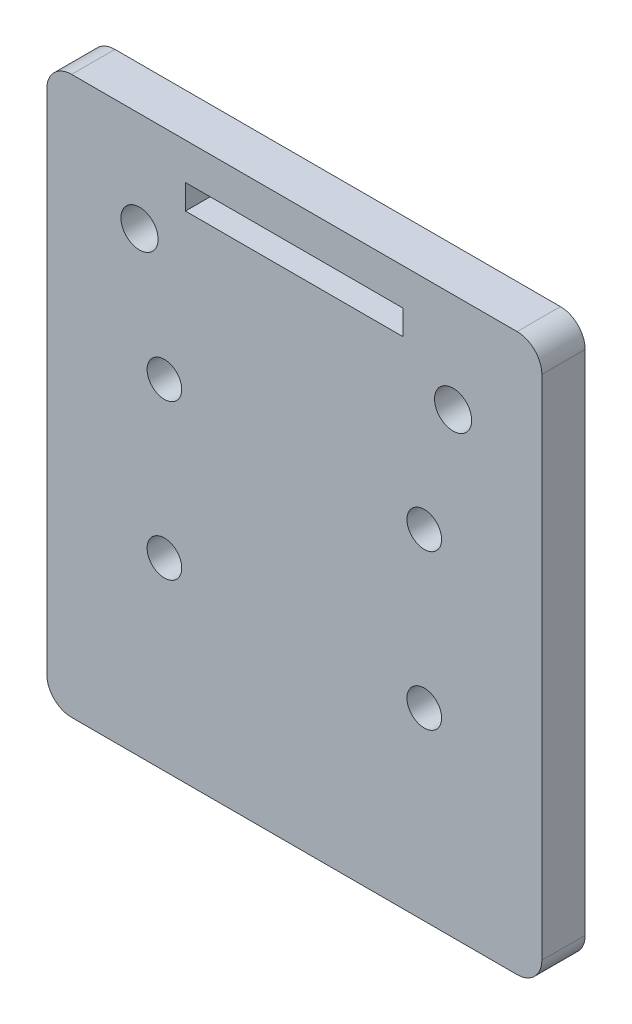
SolidWorks part; units mm, degrees
ref_plane "Front Plane" through (0, 0, 0) normal (0, 0, 1) x (1, 0, 0)
ref_plane "Top Plane" through (0, 0, 0) normal (0, 1, 0) x (1, 0, 0)
ref_plane "Right Plane" through (0, 0, 0) normal (1, 0, 0) x (0, 0, -1)
sketch "Sketch1" plane through (0, 0, 0) normal (0, 0, 1) x (1, 0, 0)
  line L1 (-2, 0) -> (-38, 0)
  line L2 (0, 2) -> (0, 43)
  line L3 (-2, 45) -> (-38, 45)
  line L4 (-40, 2) -> (-40, 43)
  arc A0 (-2, 0) -> (0, 2) centre (-2, 2) ccw
  arc A1 (-40, 2) -> (-38, 0) centre (-38, 2) ccw
  arc A2 (-2, 45) -> (0, 43) centre (-2, 43) cw
  arc A3 (-38, 45) -> (-40, 43) centre (-38, 43) ccw
  point P7 (0, 0)
  point P10 (-40, 0)
  point P13 (0, 45)
  point P16 (-40, 45)
  dimension "D3" = 2
  dimension "D1" = 40
  dimension "D2" = 45
extrude "Boss-Extrude1" add sketch "Sketch1" along normal blind 3.5 contours L2 A2 L3 A3 L4 A1 L1 A0
sketch "Sketch2" plane through (0, 0, 3.5) normal (0, 0, 1) x (1, 0, 0)
  line L0 (-20, 45) -> (-20, 0)
  line L1 (-2, 45) -> (-38, 45) construction
  line L2 (-2, 0) -> (-38, 0) construction
  line L4 (-28.8, 42.0339) -> (-11.2, 42.0339)
  line L5 (-28.8, 42.0339) -> (-28.8, 40.0339)
  line L6 (-28.8, 40.0339) -> (-11.2, 40.0339)
  line L7 (-11.2, 42.0339) -> (-11.2, 40.0339)
  point P10 (0, 0)
  dimension "D1" = 2
  dimension "D2" = 8.8
  dimension "D3" = 8.8
extrude "Cut-Extrude1" cut sketch "Sketch2" against normal through all contours L5 L6 L0 L4 | L7 L4 L0 L6
sketch "Sketch3" plane through (0, 0, 3.5) normal (0, 0, 1) x (1, 0, 0)
  circle A0 centre (-32.5126, 36.9534) radius 1.5
  circle A1 centre (-7.1726, 36.9534) radius 1.5
  dimension "D2" = 3
  dimension "D3" = 3
  dimension "D1" = 25.34
extrude "Cut-Extrude2" cut sketch "Sketch3" against normal through all contours A0 | A1
sketch "Sketch4" plane through (0, 0, 3.5) normal (0, 0, 1) x (1, 0, 0)
  circle A0 centre (-30.5, 27.4062) radius 1.4
  circle A2 centre (-30.5, 14.9062) radius 1.4
  circle A3 centre (-9.5, 14.9062) radius 1.4
  circle A4 centre (-9.5, 27.4062) radius 1.4
  point P12 (0, 0)
  dimension "D2" = 2.8
extrude "Cut-Extrude3" cut sketch "Sketch4" against normal through all contours A0 | A2 | A3 | A4
